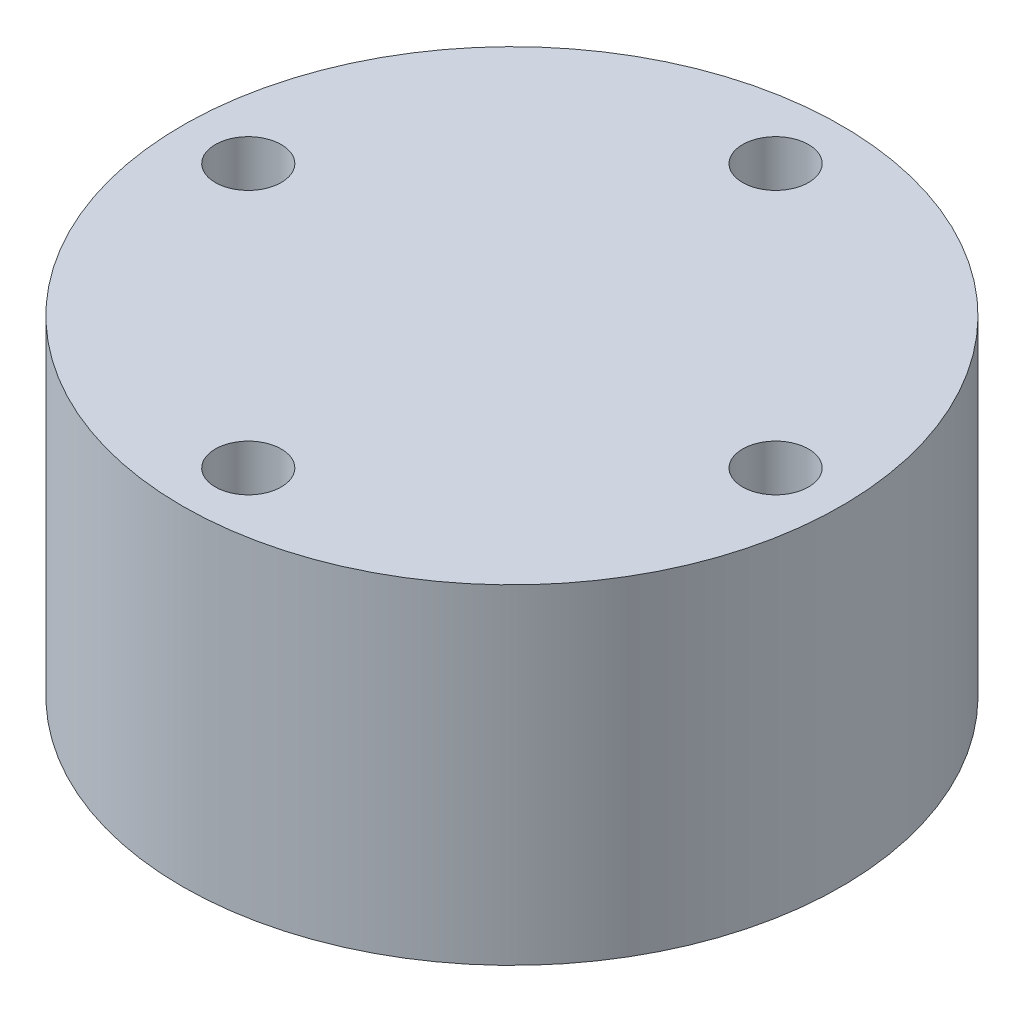
SolidWorks part; units mm, degrees
ref_plane "Front Plane" through (0, 0, 0) normal (0, 0, 1) x (1, 0, 0)
ref_plane "Top Plane" through (0, 0, 0) normal (0, 1, 0) x (1, 0, 0)
ref_plane "Right Plane" through (0, 0, 0) normal (1, 0, 0) x (0, 0, -1)
sketch "Sketch1" plane through (0, 0, 0) normal (0, 1, 0) x (1, 0, 0)
  circle A0 centre (0, 0) radius 5
  circle A1 centre (0, 0) radius 4
  circle A2 centre (0, 4) radius 0.5
  circle A3 centre (4, 0) radius 0.5
  circle A4 centre (0, -4) radius 0.5
  circle A5 centre (-4, 0) radius 0.5
extrude "Boss-Extrude1" add sketch "Sketch1" along normal blind 5 contours A5 A1 A4 A3 A2 | A0 A5 A1 A2 A3 A4
